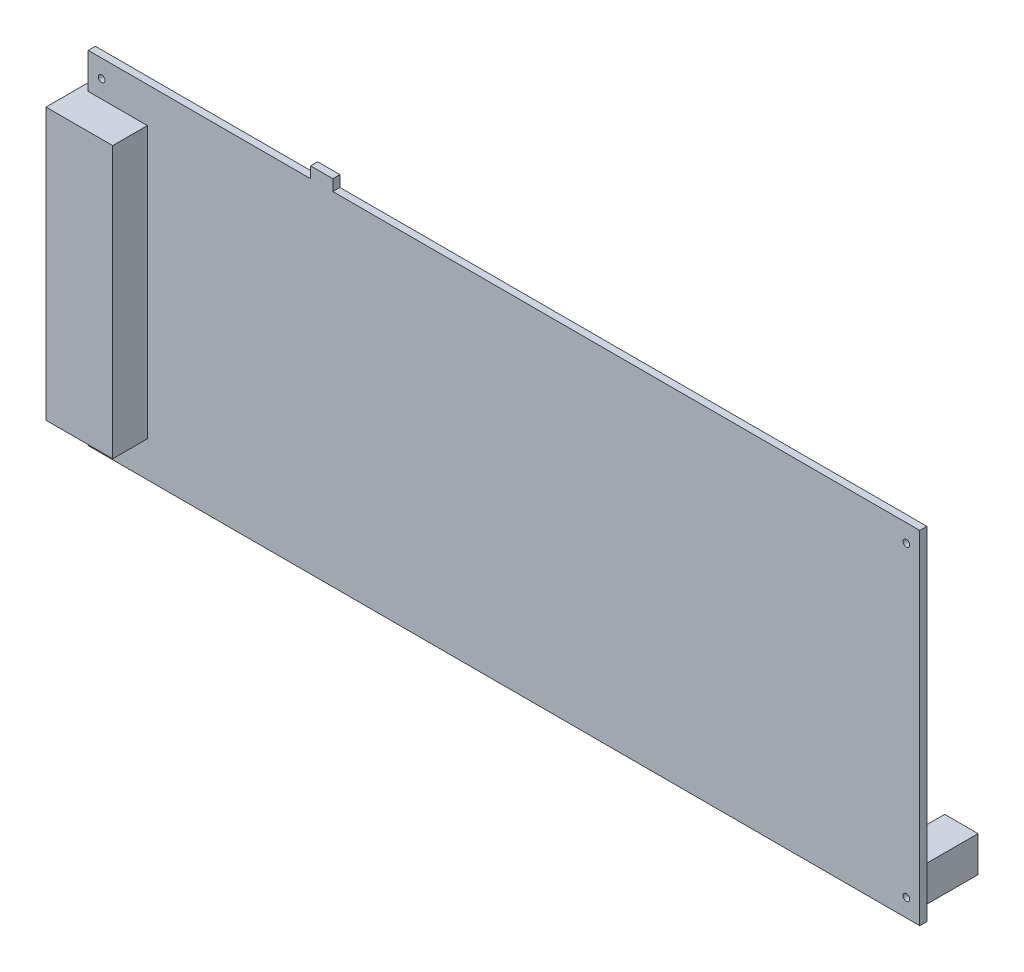
SolidWorks part; units mm, degrees
ref_plane "Спереди" through (0, 0, 0) normal (0, 0, 1) x (1, 0, 0)
ref_plane "Сверху" through (0, 0, 0) normal (0, 1, 0) x (1, 0, 0)
ref_plane "Справа" through (0, 0, 0) normal (1, 0, 0) x (0, 0, -1)
sketch "KeepOutLayer" plane through (0, 0, 0) normal (0, 0, 1) x (1, 0, 0)
  line L0 (0.0694, -77.068) -> (0.0694, -0.068)
  line L1 (0.0694, -0.068) -> (187.0694, -0.068)
  line L3 (187.0694, -77.068) -> (187.0694, -0.068)
  line L4 (0.0694, -77.068) -> (187.0694, -77.068)
  dimension "D1" = 187
  dimension "D2" = 77
  dimension "D3" = 0.068
  dimension "D4" = 0.0694
extrude "Бобышка-Вытянуть1" add sketch "KeepOutLayer" against normal blind 1.6
sketch "ViaHoleLayer" plane through (0, 0, 0) normal (0, 0, 1) x (1, 0, 0)
  line L0 (0.0694, -0.068) -> (0.0694, -77.068) construction
  line L1 (187.0694, -0.068) -> (0.0694, -0.068) construction
  line L2 (187.0694, -77.068) -> (187.0694, -0.068) construction
  line L3 (0.0694, -77.068) -> (187.0694, -77.068) construction
  circle A19 centre (3.0694, -73.068) radius 0.75
  circle A20 centre (3.0694, -4.068) radius 0.75
  circle A21 centre (184.0694, -73.068) radius 0.75
  circle A22 centre (184.0694, -4.068) radius 0.75
  dimension "D3" = 1.5
  dimension "D1" = 3
  dimension "D2" = 4
  dimension "D4" = 3
  dimension "D5" = 4
extrude "Вырез-Вытянуть1" cut sketch "ViaHoleLayer" against normal through all
sketch "Эскиз1" plane through (0, 0, 0) normal (0, 0, 1) x (1, 0, 0)
  line L0 (0.0694, -77.068) -> (187.0694, -77.068) construction
  line L1 (-1.6306, -8.068) -> (13.3694, -8.068)
  line L2 (-1.6306, -8.068) -> (-1.6306, -69.068)
  line L3 (-1.6306, -69.068) -> (13.3694, -69.068)
  line L4 (13.3694, -8.068) -> (13.3694, -69.068)
  line L5 (0.0694, -0.068) -> (0.0694, -77.068) construction
  line L6 (187.0694, -0.068) -> (0.0694, -0.068) construction
  dimension "D1" = 8
  dimension "D2" = 8
  dimension "D3" = 15
  dimension "D4" = 1.7
extrude "Бобышка-Вытянуть2" add sketch "Эскиз1" along normal blind 7.8 and the other way blind 9.6
sketch "Эскиз2" plane through (0, -0.068, 0) normal (0, 1, 0) x (1, 0, 0)
  line L0 (187.0694, 1.6) -> (0.0694, 1.6) construction
  line L1 (50.0694, 1.6) -> (55.0694, 1.6)
  line L2 (50.0694, 1.6) -> (50.0694, 0)
  line L3 (50.0694, 0) -> (55.0694, 0)
  line L4 (55.0694, 1.6) -> (55.0694, 0)
  line L5 (187.0694, 0) -> (0.0694, 0) construction
  line L7 (0.0694, 1.6) -> (0.0694, 0) construction
  dimension "D1" = 5
  dimension "D2" = 50
extrude "Бобышка-Вытянуть3" add sketch "Эскиз2" along normal blind 2.5
sketch "Эскиз4" plane through (0, 0, -1.6) normal (0, 0, -1) x (-1, 0, 0)
  line L1 (-182.0694, -78.668) -> (-174.5694, -78.668)
  line L2 (-182.0694, -78.668) -> (-182.0694, -70.668)
  line L3 (-182.0694, -70.668) -> (-174.5694, -70.668)
  line L4 (-174.5694, -78.668) -> (-174.5694, -70.668)
  line L5 (-187.0694, -77.068) -> (-187.0694, -0.068) construction
  line L6 (-0.0694, -77.068) -> (-187.0694, -77.068) construction
  dimension "D1" = 5
  dimension "D2" = 7.5
  dimension "D3" = 8
  dimension "D4" = 1.6
extrude "Бобышка-Вытянуть4" add sketch "Эскиз4" along normal blind 16.5
